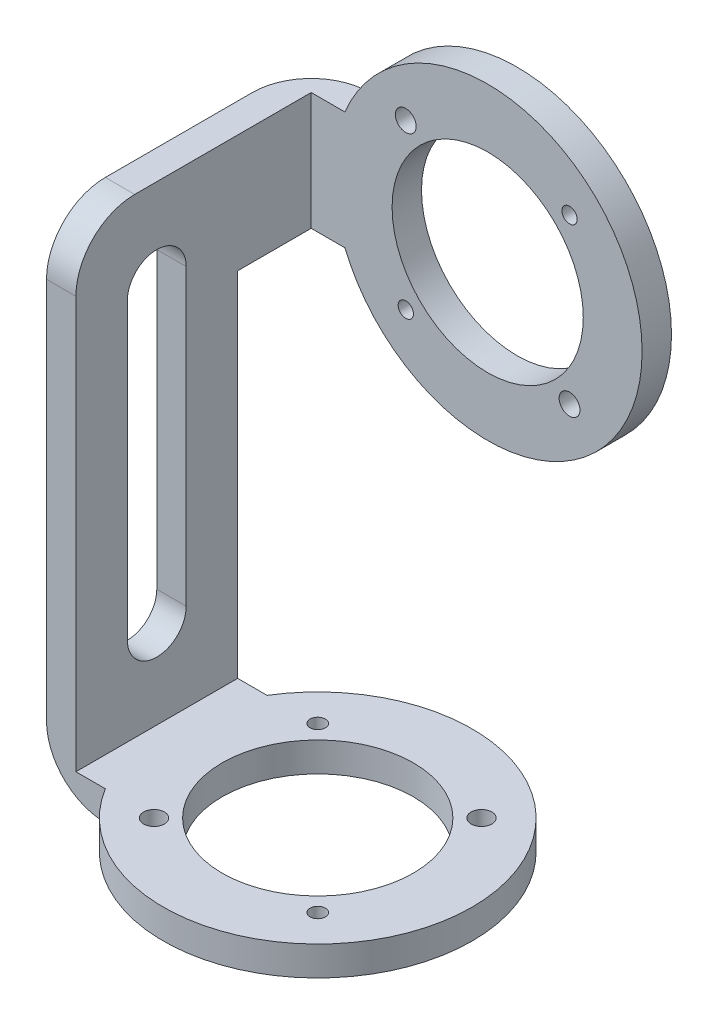
SolidWorks part; units mm, degrees
material "Cast Stainless Steel"
ref_plane "Front Plane" through (0, 0, 0) normal (0, 0, 1) x (1, 0, 0)
ref_plane "Top Plane" through (0, 0, 0) normal (0, 1, 0) x (1, 0, 0)
ref_plane "Right Plane" through (0, 0, 0) normal (1, 0, 0) x (0, 0, -1)
sketch "Sketch1" plane through (0, 0, 0) normal (0, 0, 1) x (1, 0, 0)
  line L8 (-30.8237, 12.7) -> (-38.1, 12.7)
  line L11 (-38.1, 12.7) -> (-38.1, -12.7)
  line L12 (-38.1, -12.7) -> (-30.8237, -12.7)
  circle A0 centre (-17.6777, 17.6777) radius 2.25
  circle A1 centre (17.6777, 17.6777) radius 1.65
  circle A2 centre (17.6777, -17.6777) radius 2.25
  circle A3 centre (-17.6777, -17.6777) radius 1.65
  circle A4 centre (0, 0) radius 20.6375
  circle A5 centre (0, 0) radius 33.3375
  arc A14 (-30.8237, 12.7) -> (-30.8237, -12.7) centre (0, 0) ccw
  dimension "D1" = 41.275
  dimension "D2" = 66.675
  dimension "D3" = 4.5
  dimension "D4" = 3.3
  dimension "D5" = 25
  dimension "D8" = 25
  dimension "D6" = 25
  dimension "D7" = 17.6777
  dimension "D9" = 25.4
  dimension "D10" = 12.7
  dimension "D11" = 38.1
extrude "Boss-Extrude1" add sketch "Sketch1" along normal blind 6.35 contours A5 A0 A1 A2 A3 A4 | A5 L8 L11 L12
ref_plane "Plane1" through (-38.1, 0, 0) normal (-1, 0, 0) x (0, 0, 1)
sketch "Sketch2" plane through (-38.1, 0, 0) normal (-1, 0, 0) x (0, 0, 1)
  line L0 (0, 12.7) -> (57.15, 12.7)
  line L1 (0, 33.3375) -> (0, -33.3375) construction
  line L2 (6.35, 12.7) -> (0, 12.7) construction
  line L3 (57.15, 12.7) -> (57.15, -88.9)
  line L4 (57.15, -88.9) -> (22.225, -88.9)
  line L5 (22.225, -88.9) -> (22.225, -12.7)
  line L6 (22.225, -12.7) -> (0, -12.7)
  line L7 (6.35, -12.7) -> (0, -12.7) construction
  line L8 (0, -12.7) -> (0, 12.7)
  line L9 (39.6875, -6.35) -> (39.6875, -69.85) construction
  line L10 (46.0375, -6.35) -> (46.0375, -69.85)
  line L11 (33.3375, -6.35) -> (33.3375, -69.85)
  arc A0 (46.0375, -6.35) -> (33.3375, -6.35) centre (39.6875, -6.35) ccw
  arc A1 (33.3375, -69.85) -> (46.0375, -69.85) centre (39.6875, -69.85) ccw
  point P14 (39.6875, -38.1)
  dimension "D5" = 6.35
  dimension "D6" = 19.05
  dimension "D7" = 19.05
  dimension "D1" = 57.15
  dimension "D2" = 34.925
  dimension "D3" = 101.6
  dimension "D4" = 17.4625
extrude "Boss-Extrude3" add sketch "Sketch2" along normal blind 6.35
ref_plane "Plane2" through (0, -88.9, 0) normal (0, -1, 0) x (-1, 0, 0)
sketch "Sketch4" plane through (0, -88.9, 0) normal (0, -1, 0) x (-1, 0, 0)
  line L0 (31.75, -57.15) -> (44.45, -57.15)
  line L1 (44.45, -57.15) -> (44.45, -22.225)
  line L2 (44.45, -22.225) -> (31.75, -22.225)
  line L3 (44.45, -57.15) -> (44.45, -22.225) construction
  line L5 (44.45, -22.225) -> (38.1, -22.225) construction
  circle A0 centre (21.0296, -57.3652) radius 2.25
  circle A1 centre (-14.3257, -57.3652) radius 1.65
  circle A2 centre (-14.3257, -22.0098) radius 2.25
  circle A3 centre (21.0296, -22.0098) radius 1.65
  circle A4 centre (3.3519, -39.6875) radius 20.6375
  circle A5 centre (3.3519, -39.6875) radius 33.3375
  arc A6 (31.75, -57.15) -> (31.75, -22.225) centre (3.3519, -39.6875) ccw
  point P16 (44.45, -39.6875)
  dimension "D1" = 66.675
  dimension "D2" = 41.275
  dimension "D3" = 4.5
  dimension "D4" = 3.3
  dimension "D7" = 25
  dimension "D5" = 25
  dimension "D6" = 17.6777
  dimension "D8" = 17.6777
  dimension "D9" = 12.7
  dimension "D10" = 34.925
extrude "Boss-Extrude4" add sketch "Sketch4" along normal blind 6.35 contours A5 L0 L1 L2 | A5 A0 A1 A2 A3 A4
fillet "Fillet1" radius 12.7 1 edges at (-44.45, 0, 0)
fillet "Fillet2" radius 12.7 1 edges at (-44.45, -95.25, 39.6875)
fillet "Fillet3" radius 12.7 1 edges at (-41.275, 12.7, 57.15)
